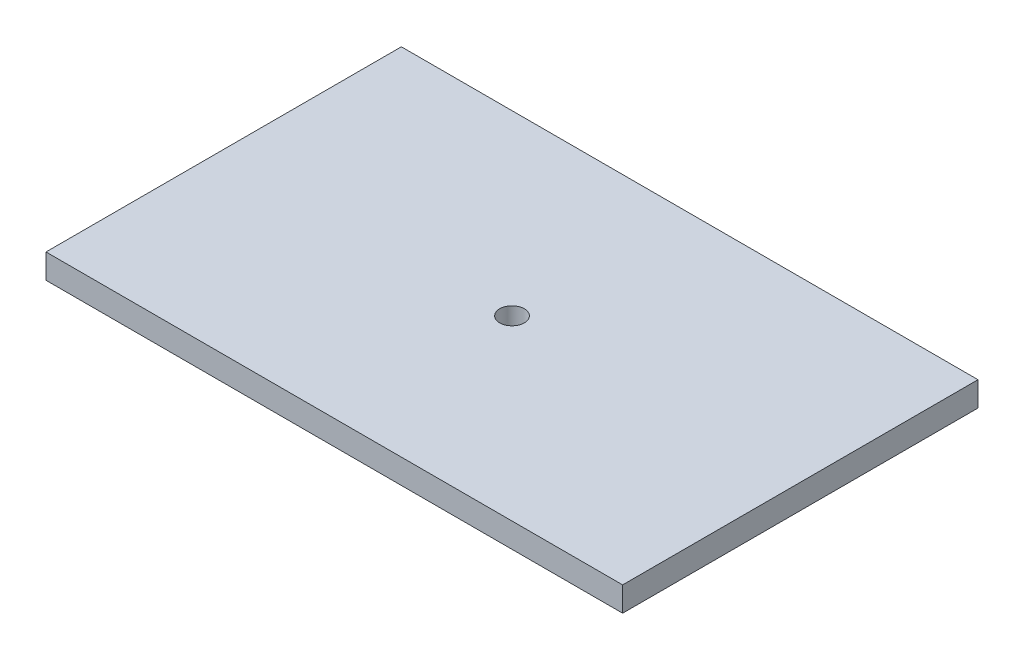
SolidWorks part; units mm, degrees
ref_plane "Front Plane" through (0, 0, 0) normal (0, 0, 1) x (1, 0, 0)
ref_plane "Top Plane" through (0, 0, 0) normal (0, 1, 0) x (1, 0, 0)
ref_plane "Right Plane" through (0, 0, 0) normal (1, 0, 0) x (0, 0, -1)
sketch "Sketch1" plane through (0, 0, 0) normal (0, 1, 0) x (1, 0, 0)
  line L1 (-117.4011, 72.3518) -> (117.4011, 72.3518)
  line L2 (-117.4011, 72.3518) -> (-117.4011, -72.3518)
  line L3 (-117.4011, -72.3518) -> (117.4011, -72.3518)
  line L4 (117.4011, 72.3518) -> (117.4011, -72.3518)
  line L5 (-117.4011, 72.3518) -> (117.4011, -72.3518) construction
  line L6 (-117.4011, -72.3518) -> (117.4011, 72.3518) construction
  point P0 (0, 0)
extrude "Boss-Extrude1" add sketch "Sketch1" along normal blind 10
sketch "Sketch2" plane through (0, 10, 0) normal (0, 1, 0) x (1, 0, 0)
  circle A0 centre (0, 0) radius 5
extrude "Cut-Extrude1" cut sketch "Sketch2" against normal blind 10
